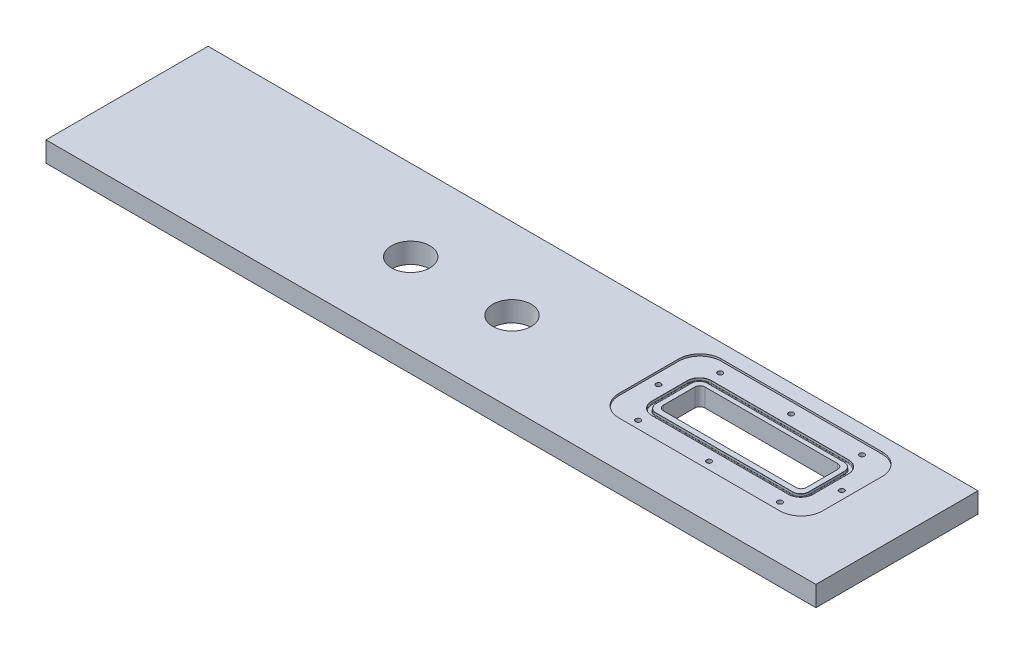
SolidWorks part; units mm, degrees
ref_plane "정면" through (0, 0, 0) normal (0, 0, 1) x (1, 0, 0)
ref_plane "윗면" through (0, 0, 0) normal (0, 1, 0) x (1, 0, 0)
ref_plane "우측면" through (0, 0, 0) normal (1, 0, 0) x (0, 0, -1)
sketch "스케치1" plane through (0, 0, 0) normal (0, 1, 0) x (1, 0, 0)
  line L1 (0, 0) -> (760, 0)
  line L2 (0, 0) -> (0, 160)
  line L3 (0, 160) -> (760, 160)
  line L4 (760, 0) -> (760, 160)
  dimension "D1" = 760
  dimension "D2" = 160
extrude "보스-돌출1" add sketch "스케치1" along normal mid plane 20
sketch "스케치2" plane through (0, 10, 0) normal (0, 1, 0) x (1, 0, 0)
  line L0 (0, 0) -> (760, 0) construction
  line L1 (0, 160) -> (0, 0) construction
  circle A0 centre (280, 80) radius 19
  circle A1 centre (380, 80) radius 19
  point P4 (0, 0)
  point P9 (0, 0)
  point P10 (0, 0)
  dimension "D4" = 38
  dimension "D1" = 80
  dimension "D2" = 280
  dimension "D3" = 100
extrude "컷-돌출1" cut sketch "스케치2" against normal through all
sketch "스케치3" plane through (0, 10, 0) normal (0, 1, 0) x (1, 0, 0)
  line L0 (0, 0) -> (760, 0) construction
  line L1 (520.5, 146) -> (679.5, 146)
  line L2 (499.5, 125) -> (499.5, 66)
  line L3 (520.5, 45) -> (679.5, 45)
  line L4 (700.5, 125) -> (700.5, 66)
  line L5 (760, 0) -> (760, 160) construction
  arc A0 (499.5, 66) -> (520.5, 45) centre (520.5, 66) ccw
  arc A1 (679.5, 146) -> (700.5, 125) centre (679.5, 125) cw
  arc A2 (679.5, 45) -> (700.5, 66) centre (679.5, 66) ccw
  arc A3 (520.5, 146) -> (499.5, 125) centre (520.5, 125) ccw
  point P12 (700.5, 146)
  point P15 (700.5, 45)
  point P18 (499.5, 146)
  dimension "D5" = 21
  dimension "D1" = 45
  dimension "D2" = 101
  dimension "D3" = 201
  dimension "D4" = 59.5
extrude "컷-돌출2" cut sketch "스케치3" against normal blind 2
sketch "스케치4" plane through (0, 8, 0) normal (0, 1, 0) x (1, 0, 0)
  line L0 (760, 0) -> (760, 160) construction
  line L1 (522.5, 122.5) -> (677.5, 122.5) construction
  line L2 (522.5, 122.5) -> (522.5, 67.5) construction
  line L3 (522.5, 67.5) -> (677.5, 67.5) construction
  line L4 (677.5, 122.5) -> (677.5, 67.5) construction
  line L10 (532.5, 124.55) -> (667.5, 124.55)
  line L11 (679.55, 112.5) -> (679.55, 77.5)
  line L12 (532.5, 65.45) -> (667.5, 65.45)
  line L13 (520.45, 112.5) -> (520.45, 77.5)
  line L14 (532.5, 120.45) -> (667.5, 120.45)
  line L15 (675.45, 112.5) -> (675.45, 77.5)
  line L16 (532.5, 69.55) -> (667.5, 69.55)
  line L17 (524.55, 112.5) -> (524.55, 77.5)
  line L18 (520.45, 124.55) -> (679.55, 124.55) construction
  line L19 (520.45, 124.55) -> (520.45, 65.45) construction
  line L20 (520.45, 65.45) -> (679.55, 65.45) construction
  line L21 (679.55, 124.55) -> (679.55, 65.45) construction
  line L22 (524.55, 120.45) -> (675.45, 120.45) construction
  line L23 (675.45, 120.45) -> (675.45, 69.55) construction
  line L24 (524.55, 69.55) -> (675.45, 69.55) construction
  line L25 (524.55, 120.45) -> (524.55, 69.55) construction
  line L26 (0, 0) -> (760, 0) construction
  arc A0 (532.5, 124.55) -> (520.45, 112.5) centre (532.5, 112.5) ccw
  arc A1 (532.5, 65.45) -> (520.45, 77.5) centre (532.5, 77.5) cw
  arc A2 (679.55, 77.5) -> (667.5, 65.45) centre (667.5, 77.5) cw
  arc A3 (667.5, 124.55) -> (679.55, 112.5) centre (667.5, 112.5) cw
  arc A4 (667.5, 120.45) -> (675.45, 112.5) centre (667.5, 112.5) cw
  arc A5 (675.45, 77.5) -> (667.5, 69.55) centre (667.5, 77.5) cw
  arc A6 (532.5, 69.55) -> (524.55, 77.5) centre (532.5, 77.5) cw
  arc A7 (532.5, 120.45) -> (524.55, 112.5) centre (532.5, 112.5) ccw
  dimension "D7" = 12.05
  dimension "D8" = 7.95
  dimension "D1" = 82.5
  dimension "D2" = 55
  dimension "D3" = 67.5
  dimension "D4" = 155
  dimension "D5" = 2.05
  dimension "D6" = 2.05
extrude "컷-돌출4" cut sketch "스케치4" against normal blind 2.7
sketch "스케치5" plane through (0, 8, 0) normal (0, 1, 0) x (1, 0, 0)
  line L0 (0, 0) -> (760, 0) construction
  line L1 (534.5, 116) -> (665.5, 116)
  line L2 (529.5, 111) -> (529.5, 80)
  line L3 (534.5, 75) -> (665.5, 75)
  line L4 (670.5, 111) -> (670.5, 80)
  line L5 (760, 0) -> (760, 160) construction
  arc A0 (529.5, 80) -> (534.5, 75) centre (534.5, 80) ccw
  arc A1 (665.5, 75) -> (670.5, 80) centre (665.5, 80) ccw
  arc A2 (665.5, 116) -> (670.5, 111) centre (665.5, 111) cw
  arc A3 (534.5, 116) -> (529.5, 111) centre (534.5, 111) ccw
  dimension "D5" = 5
  dimension "D1" = 75
  dimension "D2" = 41
  dimension "D3" = 141
  dimension "D4" = 89.5
extrude "컷-돌출5" cut sketch "스케치5" against normal through all
sketch "스케치6" plane through (0, 8, 0) normal (0, 1, 0) x (1, 0, 0)
  line L0 (0, 160) -> (0, 0) construction
  line L1 (0, 0) -> (760, 0) construction
  point P0 (530, 135.5)
  point P1 (600, 135.5)
  point P2 (670, 135.5)
  point P3 (670, 54.5)
  point P4 (600, 54.5)
  point P5 (530, 54.5)
  point P6 (509.5, 95)
  point P7 (690.5, 95)
  dimension "D1" = 20.5
  dimension "D2" = 530
  dimension "D3" = 70
  dimension "D4" = 70
  dimension "D5" = 40.5
  dimension "D6" = 54.5
  dimension "D7" = 40.5
  dimension "D8" = 20.5
hole_wizard "M6 나사 구멍1" positions "스케치6" profile "스케치7" tap size "M6" standard "ISO"
sketch "스케치7" plane through (530, 8, -135.5) normal (1, 0, 0) x (0, 0, 1)
  line L0 (0, 0) -> (0, 16.5022)
  line L1 (0, 16.5022) -> (2.5, 15)
  line L2 (2.5, 15) -> (2.5, 0)
  line L5 (2.5, 0) -> (0, 0)
  line L10 (0, 16.5022) -> (-2.5, 15) construction
  line L11 (0, -6.35) -> (0, 107.95) construction
  dimension "탭 드릴 지름" = 5
  dimension "탭 드릴 깊이" = 15
  dimension "드릴 각도" = 118
cosmetic thread "구멍 나사산1" parameters "D1"=10, "D2"=6
cosmetic thread "구멍 나사산2" parameters "D1"=10, "D2"=6
cosmetic thread "구멍 나사산3" parameters "D1"=10, "D2"=6
cosmetic thread "구멍 나사산4" parameters "D1"=10, "D2"=6
cosmetic thread "구멍 나사산5" parameters "D1"=10, "D2"=6
cosmetic thread "구멍 나사산6" parameters "D1"=10, "D2"=6
cosmetic thread "구멍 나사산7" parameters "D1"=10, "D2"=6
cosmetic thread "구멍 나사산8" parameters "D1"=10, "D2"=6
fillet "필렛1" radius 0.13 8 edges at (676.0206, 8, -121.0206) (679.55, 8, -95) (676.0206, 8, -68.9794) (600, 8, -65.45) (523.9794, 8, -68.9794) (520.45, 8, -95) (523.9794, 8, -121.0206) (600, 8, -124.55)
fillet "필렛2" radius 0.5 8 edges at (600, 5.3, -124.55) (676.0206, 5.3, -121.0206) (679.55, 5.3, -95) (676.0206, 5.3, -68.9794) (600, 5.3, -65.45) (523.9794, 5.3, -68.9794) (520.45, 5.3, -95) (523.9794, 5.3, -121.0206)
fillet "필렛3" radius 0.5 8 edges at (526.8785, 5.3, -118.1215) (600, 5.3, -120.45) (673.1215, 5.3, -118.1215) (675.45, 5.3, -95) (673.1215, 5.3, -71.8785) (600, 5.3, -69.55) (526.8785, 5.3, -71.8785) (524.55, 5.3, -95)
fillet "필렛4" radius 0.13 8 edges at (526.8785, 8, -118.1215) (600, 8, -120.45) (673.1215, 8, -118.1215) (675.45, 8, -95) (673.1215, 8, -71.8785) (600, 8, -69.55) (526.8785, 8, -71.8785) (524.55, 8, -95)
